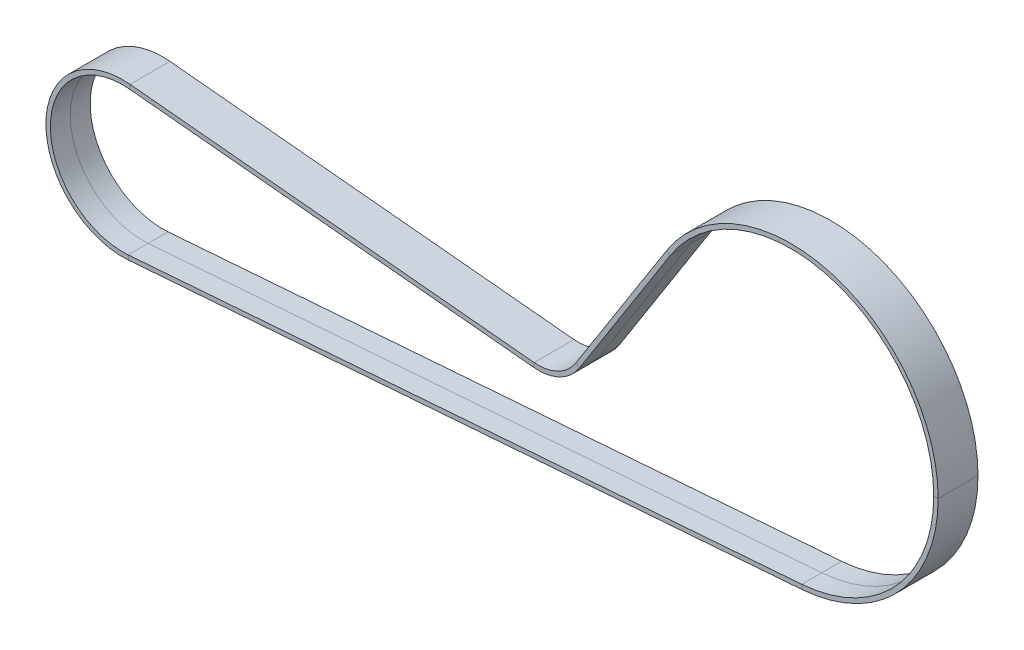
SolidWorks part; units mm, degrees
ref_plane "Front Plane" through (0, 0, 0) normal (0, 0, 1) x (1, 0, 0)
ref_plane "Top Plane" through (0, 0, 0) normal (0, 1, 0) x (1, 0, 0)
ref_plane "Right Plane" through (0, 0, 0) normal (1, 0, 0) x (0, 0, -1)
sketch "Sketch2" plane through (0, 0, 0) normal (0, 0, 1) x (1, 0, 0)
  line L0 (0, 0) -> (1, 0) construction
  line L1 (0, 0) -> (0, 1) construction
  line L2 (2.4598, -32.1661) -> (-149.6405, -43.7974)
  line L3 (-149.3202, -11.2302) -> (-58.0833, -20.0152)
  line L4 (-47.7465, -14.9681) -> (-27.2229, 17.3096)
  arc A0 (-27.2229, 17.3096) -> (2.4598, -32.1661) centre (0, 0) cw
  arc A1 (-149.6405, -43.7974) -> (-149.3202, -11.2302) centre (-150.8868, -27.5) cw
  arc A2 (-58.0833, -20.0152) -> (-47.7465, -14.9681) centre (-57.029, -9.0658) ccw
sketch "Sketch3" plane through (0, 0, 0) normal (0, 1, 0) x (1, 0, 0)
  line L0 (32.26, 0) -> (32.26, -4.5)
  line L1 (-27.2229, 0) -> (32.26, 0) construction
  line L2 (32.26, -4.5) -> (33.26, -4.5)
  line L3 (33.26, -4.5) -> (33.26, 4.5)
  line L4 (33.26, 4.5) -> (32.26, 4.5)
  line L5 (32.26, 4.5) -> (32.26, 0)
  point P8 (33.26, 0)
  dimension "D1" = 1
  dimension "D2" = 9
  dimension "D3" = 32.26
sweep "Sweep1" add profiles "Sketch3" path "Sketch2"
